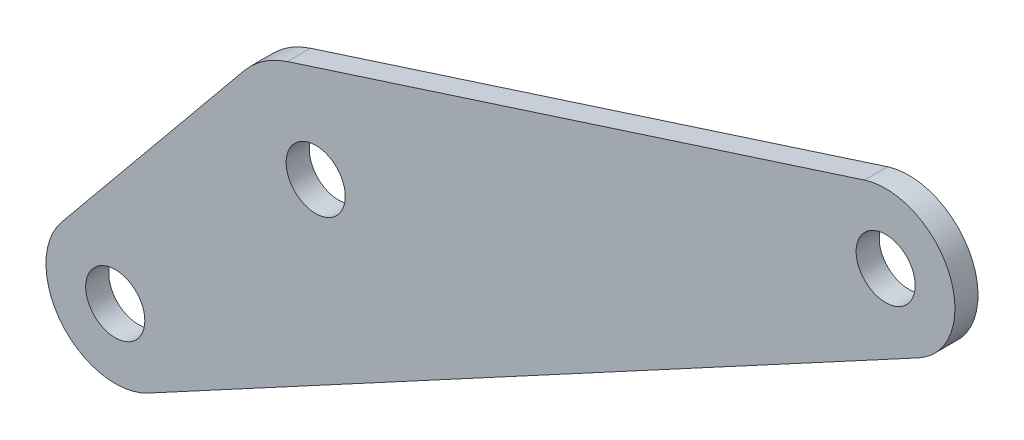
SolidWorks part; units mm, degrees
ref_plane "Front Plane" through (0, 0, 0) normal (0, 0, 1) x (1, 0, 0)
ref_plane "Top Plane" through (0, 0, 0) normal (0, 1, 0) x (1, 0, 0)
ref_plane "Right Plane" through (0, 0, 0) normal (1, 0, 0) x (0, 0, -1)
sketch "Sketch1" plane through (0, 0, 0) normal (0, 0, 1) x (1, 0, 0)
  line L0 (-17.4609, -11.2661) -> (-4.9086, 4.0285)
  line L1 (37.7194, 18.8206) -> (-1.9468, 6.0442)
  line L2 (41.441, 10.0962) -> (-11.518, -18.4788)
  circle A0 centre (0, 0) radius 2.032
  circle A1 centre (-13.7795, -14.2875) radius 2.032
  circle A3 centre (39.1795, 14.2875) radius 2.032
  arc A4 (-1.9468, 6.0442) -> (-4.9086, 4.0285) centre (0, 0) ccw
  arc A5 (-17.4609, -11.2661) -> (-11.518, -18.4788) centre (-13.7795, -14.2875) ccw
  arc A6 (37.7194, 18.8206) -> (41.441, 10.0962) centre (39.1795, 14.2875) cw
  circle A7 centre (39.1795, 14.2875) radius 2.032 construction
  circle A8 centre (-13.7795, -14.2875) radius 2.032 construction
  dimension "D1" = 4.064
  dimension "D2" = 4.064
  dimension "D3" = 6.35
  dimension "D4" = 4.7625
extrude "Boss-Extrude1" add sketch "Sketch1" along normal blind 1.5875
